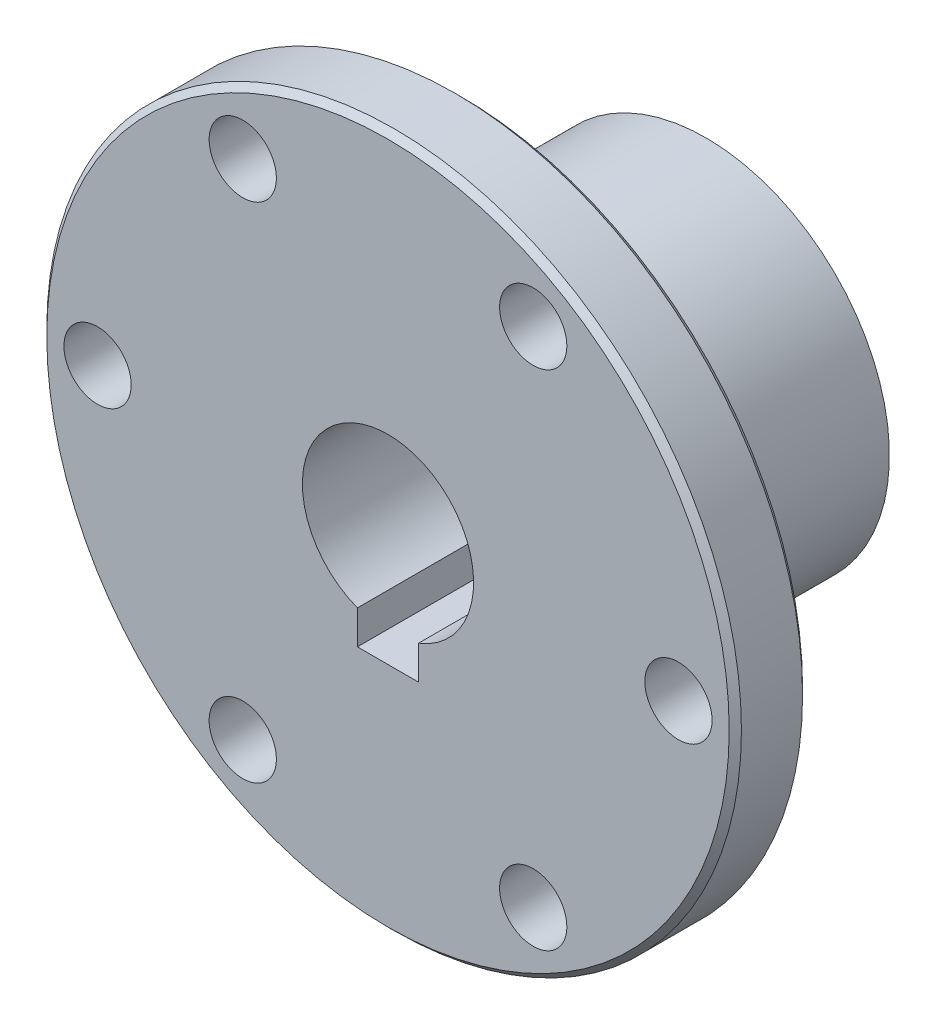
SolidWorks part; units mm, degrees
material "AISI Type 316L stainless steel"
ref_plane "Front Plane" through (0, 0, 0) normal (0, 0, 1) x (1, 0, 0)
ref_plane "Top Plane" through (0, 0, 0) normal (0, 1, 0) x (1, 0, 0)
ref_plane "Right Plane" through (0, 0, 0) normal (1, 0, 0) x (0, 0, -1)
sketch "Sketch1" plane through (0, 0, 0) normal (0, 0, 1) x (1, 0, 0)
  circle A0 centre (0, 0) radius 28.4
  dimension "D1" = 56.8
extrude "Boss-Extrude1" add sketch "Sketch1" along normal blind 26
sketch "Sketch2" plane through (0, 0, 0) normal (0, 0, -1) x (-1, 0, 0)
  circle A0 centre (0, 0) radius 15
  dimension "D1" = 30
extrude "Cut-Extrude1" cut sketch "Sketch2" against normal offset from surface (20 mm away) 6 flip side to cut up to face at (28.4, 0, 26)
sketch "Sketch3" plane through (0, 0, 0) normal (0, 0, -1) x (-1, 0, 0)
  line L0 (2.5, -6.5383) -> (2.5, -9.3)
  line L3 (-2.5, -9.3) -> (2.5, -9.3)
  line L9 (-2.5, -6.5383) -> (-2.5, -9.3)
  arc A0 (2.5, -6.5383) -> (-2.5, -6.5383) centre (0, 0) ccw
  point P1 (0, -9.3)
  dimension "D1" = 14
  dimension "D2" = 9.3
  dimension "D3" = 5
extrude "Cut-Extrude2" cut sketch "Sketch3" against normal through all
chamfer "Chamfer1" distance 0.5 angle 45 2 edges at (28.4, 0, 20) (28.4, 0, 26)
sketch "Sketch6" plane through (0, 0, 26) normal (0, 0, 1) x (1, 0, 0)
  circle A1 centre (0, 0) radius 23.75 construction
  point P4 (23.75, 0)
  dimension "D1" = 47.5
hole_wizard "M5 Clearance Hole1" positions "Sketch6" profile "Sketch5" hole size "M5" standard "ANSI Metric" end condition through all
sketch "Sketch5" plane through (23.75, 0, 26) normal (1, 0, 0) x (0, -1, 0)
  line L0 (0, 0) -> (0, 26)
  line L1 (0, 26) -> (2.75, 26)
  line L2 (2.75, 26) -> (2.75, 0)
  line L5 (2.75, 0) -> (0, 0)
  line L11 (0, -6.35) -> (0, 107.95) construction
  dimension "Thru Hole Dia." = 5.5
  dimension "Thru Hole Depth" = 26
pattern_circular "CirPattern1" count 6 over 360 about axis through (0, 0, 0) along (0, 0, 1) of "M5 Clearance Hole1"
sketch "Sketch9" plane through (0, 0, 0) normal (1, 0, 0) x (0, 0, -1)
  circle A0 centre (-10.2, 0) radius 4
  dimension "D1" = 8
  dimension "D2" = 10.2
extrude "Cut-Extrude3" cut sketch "Sketch9" against normal through all
